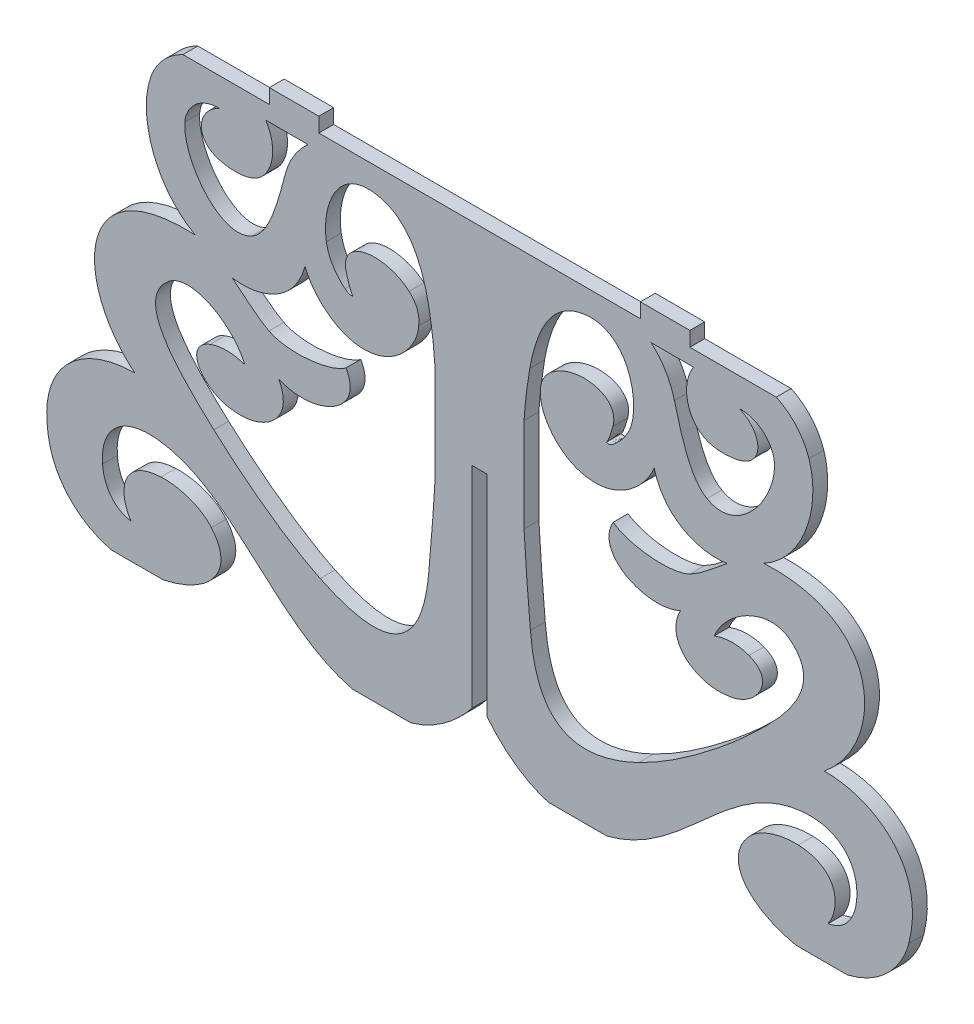
SolidWorks part; units mm, degrees
ref_plane "Plano frontal" through (0, 0, 0) normal (0, 0, 1) x (1, 0, 0)
ref_plane "Plano superior" through (0, 0, 0) normal (0, 1, 0) x (1, 0, 0)
ref_plane "Plano direito" through (0, 0, 0) normal (1, 0, 0) x (0, 0, -1)
sketch "Model" plane through (0, 0, 0) normal (0, 0, 1) x (1, 0, 0)
  line L0 (-25.299, -80.6801) -> (18.0344, -80.6801)
  line L21 (39.01, -143.3136) -> (45.9466, -143.3136)
  line L22 (36.3446, -80.6801) -> (24.701, -80.6801)
  line L23 (24.701, -80.6801) -> (24.701, -78.7123)
  line L24 (24.701, -78.7123) -> (18.0344, -78.7123)
  line L25 (18.0344, -78.7123) -> (18.0344, -80.6801)
  line L26 (-25.299, -80.6801) -> (-25.299, -78.7123)
  line L27 (-25.299, -78.7123) -> (-31.9656, -78.7123)
  line L28 (-31.9656, -78.7123) -> (-31.9656, -80.6801)
  line L29 (-31.9656, -80.6801) -> (-43.6092, -80.6801)
  line L30 (-53.2112, -143.3136) -> (-46.2746, -143.3136)
  line L31 (-20.7922, -143.3136) -> (-12.8827, -143.3136)
  line L32 (-4.6323, -137.4568) -> (-4.6323, -109.1511)
  line L33 (-4.6323, -109.1511) -> (-2.6323, -109.1511)
  line L34 (-2.6323, -109.1511) -> (-2.6323, -137.4568)
  line L35 (5.6181, -143.3136) -> (13.5276, -143.3136)
  line L36 (-26.7511, -82.7498) -> (-32.4569, -82.7498)
  line L37 (-9.6217, -113.0468) -> (-9.6217, -100.393)
  line L38 (19.4865, -82.7498) -> (25.1923, -82.7498)
  line L39 (2.3571, -113.0468) -> (2.3571, -100.393)
  spline S82 degree 3 poles (13.5276, -143.3136) (24.0999, -140.6337) (29.5908, -128.3406) (39.7847, -127.3008) knots 0 0 0 0 0.02439 0.02439 0.02439 0.02439
  spline S83 degree 3 poles (39.7847, -127.3008) (44.8462, -126.7846) (47.5126, -129.843) (47.1792, -133.8877) knots 0.02439 0.02439 0.02439 0.02439 0.04878 0.04878 0.04878 0.04878
  spline S84 degree 3 poles (47.1792, -133.8877) (46.9993, -136.07) (45.898, -138.1875) (43.3255, -138.6275) knots 0.04878 0.04878 0.04878 0.04878 0.073171 0.073171 0.073171 0.073171
  spline S85 degree 3 poles (43.3255, -138.6275) (45.091, -136.0452) (44.7729, -131.7145) (39.3053, -131.4591) knots 0.073171 0.073171 0.073171 0.073171 0.097561 0.097561 0.097561 0.097561
  spline S86 degree 3 poles (39.3053, -131.4591) (36.7984, -131.342) (33.9868, -132.244) (32.5083, -133.9746) knots 0.097561 0.097561 0.097561 0.097561 0.121951 0.121951 0.121951 0.121951
  spline S87 degree 3 poles (32.5083, -133.9746) (29.0675, -138.0023) (32.9753, -142.0567) (39.01, -143.3136) knots 0.121951 0.121951 0.121951 0.121951 0.146341 0.146341 0.146341 0.146341
  spline S88 degree 3 poles (45.9466, -143.3136) (50.593, -142.1908) (53.3599, -138.7763) (54.1991, -135.5231) knots 0.170732 0.170732 0.170732 0.170732 0.195122 0.195122 0.195122 0.195122
  spline S89 degree 3 poles (54.1991, -135.5231) (56.5947, -126.2354) (50.0219, -121.0373) (42.8047, -121.0878) knots 0.195122 0.195122 0.195122 0.195122 0.219512 0.219512 0.219512 0.219512
  spline S90 degree 3 poles (42.8047, -121.0878) (51.071, -114.4578) (51.1176, -100.1132) (34.6597, -100.9082) knots 0.219512 0.219512 0.219512 0.219512 0.243902 0.243902 0.243902 0.243902
  spline S91 degree 3 poles (34.6597, -100.9082) (39.9859, -98.0452) (42.4387, -90.8382) (40.748, -85.6548) knots 0.243902 0.243902 0.243902 0.243902 0.268293 0.268293 0.268293 0.268293
  spline S92 degree 3 poles (40.748, -85.6548) (40.1089, -83.6954) (38.6749, -81.7888) (36.3446, -80.6801) knots 0.268293 0.268293 0.268293 0.268293 0.292683 0.292683 0.292683 0.292683
  spline S94 degree 3 poles (-43.6092, -80.6801) (-45.9395, -81.7888) (-47.3735, -83.6954) (-48.0126, -85.6548) knots 0.512195 0.512195 0.512195 0.512195 0.536585 0.536585 0.536585 0.536585
  spline S95 degree 3 poles (-48.0126, -85.6548) (-49.7033, -90.8382) (-47.2505, -98.0452) (-41.9243, -100.9082) knots 0.536585 0.536585 0.536585 0.536585 0.560976 0.560976 0.560976 0.560976
  spline S96 degree 3 poles (-41.9243, -100.9082) (-58.3822, -100.1132) (-58.3356, -114.4578) (-50.0693, -121.0878) knots 0.560976 0.560976 0.560976 0.560976 0.585366 0.585366 0.585366 0.585366
  spline S97 degree 3 poles (-50.0693, -121.0878) (-57.2865, -121.0373) (-63.8593, -126.2354) (-61.4637, -135.5231) knots 0.585366 0.585366 0.585366 0.585366 0.609756 0.609756 0.609756 0.609756
  spline S98 degree 3 poles (-61.4637, -135.5231) (-60.6245, -138.7763) (-57.8576, -142.1908) (-53.2112, -143.3136) knots 0.609756 0.609756 0.609756 0.609756 0.634146 0.634146 0.634146 0.634146
  spline S99 degree 3 poles (-46.2746, -143.3136) (-40.2399, -142.0567) (-36.3321, -138.0023) (-39.7729, -133.9746) knots 0.658537 0.658537 0.658537 0.658537 0.682927 0.682927 0.682927 0.682927
  spline S100 degree 3 poles (-39.7729, -133.9746) (-41.2514, -132.244) (-44.063, -131.342) (-46.5699, -131.4591) knots 0.682927 0.682927 0.682927 0.682927 0.707317 0.707317 0.707317 0.707317
  spline S101 degree 3 poles (-46.5699, -131.4591) (-52.0375, -131.7145) (-52.3556, -136.0452) (-50.5901, -138.6275) knots 0.707317 0.707317 0.707317 0.707317 0.731707 0.731707 0.731707 0.731707
  spline S102 degree 3 poles (-50.5901, -138.6275) (-53.1626, -138.1875) (-54.2639, -136.07) (-54.4438, -133.8877) knots 0.731707 0.731707 0.731707 0.731707 0.756098 0.756098 0.756098 0.756098
  spline S103 degree 3 poles (-54.4438, -133.8877) (-54.7772, -129.843) (-52.1108, -126.7846) (-47.0493, -127.3008) knots 0.756098 0.756098 0.756098 0.756098 0.780488 0.780488 0.780488 0.780488
  spline S104 degree 3 poles (-47.0493, -127.3008) (-36.8554, -128.3406) (-31.3645, -140.6337) (-20.7922, -143.3136) knots 0.780488 0.780488 0.780488 0.780488 0.804878 0.804878 0.804878 0.804878
  spline S105 degree 3 poles (-12.8827, -143.3136) (-8.8659, -142.1463) (-6.0526, -139.244) (-4.6323, -137.4568) knots 0.829268 0.829268 0.829268 0.829268 0.853659 0.853659 0.853659 0.853659
  spline S106 degree 3 poles (-2.6323, -137.4568) (-1.212, -139.244) (1.6013, -142.1463) (5.6181, -143.3136) knots 0.926829 0.926829 0.926829 0.926829 0.95122 0.95122 0.95122 0.95122
  spline S107 degree 3 poles (-32.4569, -82.7498) (-31.1733, -84.7323) (-31.2313, -87.2662) (-32.4844, -89.0266) knots 0 0 0 0 0.111111 0.111111 0.111111 0.111111
  spline S108 degree 3 poles (-32.4844, -89.0266) (-33.3768, -90.2802) (-35.0403, -91.1102) (-37.9276, -90.6875) knots 0.111111 0.111111 0.111111 0.111111 0.222222 0.222222 0.222222 0.222222
  spline S109 degree 3 poles (-37.9276, -90.6875) (-42.1519, -90.0692) (-41.9903, -85.9673) (-38.6474, -84.4976) knots 0.222222 0.222222 0.222222 0.222222 0.333333 0.333333 0.333333 0.333333
  spline S110 degree 3 poles (-38.6474, -84.4976) (-41.6734, -84.4609) (-43.2427, -86.7759) (-43.3562, -88.4235) knots 0.333333 0.333333 0.333333 0.333333 0.444444 0.444444 0.444444 0.444444
  spline S111 degree 3 poles (-43.3562, -88.4235) (-43.6636, -92.8804) (-38.5123, -99.6442) (-34.2704, -97.1791) knots 0.444444 0.444444 0.444444 0.444444 0.555556 0.555556 0.555556 0.555556
  spline S112 degree 3 poles (-34.2704, -97.1791) (-32.5007, -96.1507) (-31.3381, -93.6932) (-29.8837, -87.9524) knots 0.555556 0.555556 0.555556 0.555556 0.666667 0.666667 0.666667 0.666667
  spline S113 degree 3 poles (-29.8837, -87.9524) (-29.3667, -85.9116) (-28.3138, -84.1273) (-26.7511, -82.7498) knots 0.666667 0.666667 0.666667 0.666667 0.777778 0.777778 0.777778 0.777778
  spline S114 degree 3 poles (-9.6217, -100.393) (-9.7726, -98.2023) (-10.0208, -96.045) (-10.3939, -93.9386) knots 0.041667 0.041667 0.041667 0.041667 0.083333 0.083333 0.083333 0.083333
  spline S115 degree 3 poles (-10.3939, -93.9386) (-11.331, -88.6476) (-13.5268, -84.1713) (-18.2928, -83.8913) knots 0.083333 0.083333 0.083333 0.083333 0.125 0.125 0.125 0.125
  spline S116 degree 3 poles (-18.2928, -83.8913) (-23.0171, -83.6137) (-24.9083, -88.9647) (-24.2808, -92.8525) knots 0.125 0.125 0.125 0.125 0.166667 0.166667 0.166667 0.166667
  spline S117 degree 3 poles (-24.2808, -92.8525) (-24.0259, -94.4318) (-23.2335, -95.8334) (-21.7588, -97.078) knots 0.166667 0.166667 0.166667 0.166667 0.208333 0.208333 0.208333 0.208333
  spline S118 degree 3 poles (-21.7588, -97.078) (-21.3405, -97.4311) (-20.9898, -97.5247) (-20.7021, -97.3929) knots 0.208333 0.208333 0.208333 0.208333 0.25 0.25 0.25 0.25
  spline S119 degree 3 poles (-20.7021, -97.3929) (-20.8973, -97.2341) (-21.1963, -96.5924) (-21.5905, -95.1207) knots 0.25 0.25 0.25 0.25 0.291667 0.291667 0.291667 0.291667
  spline S120 degree 3 poles (-21.5905, -95.1207) (-22.6756, -91.07) (-16.2984, -90.2558) (-13.1252, -93.083) knots 0.291667 0.291667 0.291667 0.291667 0.333333 0.333333 0.333333 0.333333
  spline S121 degree 3 poles (-13.1252, -93.083) (-12.1537, -93.9486) (-11.6464, -95.1051) (-11.8511, -96.4742) knots 0.333333 0.333333 0.333333 0.333333 0.375 0.375 0.375 0.375
  spline S122 degree 3 poles (-11.8511, -96.4742) (-11.9194, -98.9913) (-15.0834, -103.3668) (-20.0254, -102.8281) knots 0.375 0.375 0.375 0.375 0.416667 0.416667 0.416667 0.416667
  spline S123 degree 3 poles (-20.0254, -102.8281) (-23.5148, -102.4476) (-26.3139, -99.4595) (-27.1557, -97.1641) knots 0.416667 0.416667 0.416667 0.416667 0.458333 0.458333 0.458333 0.458333
  spline S124 degree 3 poles (-27.1557, -97.1641) (-28.5683, -102.4552) (-33.5101, -103.9638) (-36.9867, -103.4069) knots 0.458333 0.458333 0.458333 0.458333 0.5 0.5 0.5 0.5
  spline S125 degree 3 poles (-36.9867, -103.4069) (-35.3064, -104.7163) (-33.7715, -106.2083) (-32.007, -107.1244) knots 0.5 0.5 0.5 0.5 0.541667 0.541667 0.541667 0.541667
  spline S126 degree 3 poles (-32.007, -107.1244) (-29.3781, -108.4896) (-23.7227, -107.8286) (-21.6381, -106.2645) knots 0.541667 0.541667 0.541667 0.541667 0.583333 0.583333 0.583333 0.583333
  spline S127 degree 3 poles (-21.6381, -106.2645) (-18.9894, -110.8906) (-26.1931, -114.1757) (-30.699, -112.0561) knots 0.583333 0.583333 0.583333 0.583333 0.625 0.625 0.625 0.625
  spline S128 degree 3 poles (-30.699, -112.0561) (-28.4119, -116.3864) (-32.9424, -119.4988) (-37.1074, -118.7844) knots 0.625 0.625 0.625 0.625 0.666667 0.666667 0.666667 0.666667
  spline S129 degree 3 poles (-37.1074, -118.7844) (-40.7542, -118.4687) (-43.8613, -114.1754) (-39.9339, -112.6598) knots 0.666667 0.666667 0.666667 0.666667 0.708333 0.708333 0.708333 0.708333
  spline S130 degree 3 poles (-39.9339, -112.6598) (-38.6761, -112.1744) (-36.9586, -112.0849) (-35.2485, -112.716) knots 0.708333 0.708333 0.708333 0.708333 0.75 0.75 0.75 0.75
  spline S131 degree 3 poles (-35.2485, -112.716) (-36.9784, -108.7073) (-42.6099, -105.7375) (-45.5096, -108.0977) knots 0.75 0.75 0.75 0.75 0.791667 0.791667 0.791667 0.791667
  spline S132 degree 3 poles (-45.5096, -108.0977) (-50.1258, -111.855) (-44.9673, -117.3572) (-39.4446, -122.3875) knots 0.791667 0.791667 0.791667 0.791667 0.833333 0.833333 0.833333 0.833333
  spline S133 degree 3 poles (-39.4446, -122.3875) (-36.6658, -124.9185) (-30.845, -129.788) (-25.1107, -132.5742) knots 0.833333 0.833333 0.833333 0.833333 0.875 0.875 0.875 0.875
  spline S134 degree 3 poles (-25.1107, -132.5742) (-13.1524, -138.3844) (-10.9954, -130.4623) (-10.4758, -124.4534) knots 0.875 0.875 0.875 0.875 0.916667 0.916667 0.916667 0.916667
  spline S135 degree 3 poles (-10.4758, -124.4534) (-10.1517, -120.706) (-9.8219, -116.8755) (-9.6217, -113.0468) knots 0.916667 0.916667 0.916667 0.916667 1 1 1 1
  spline S136 degree 3 poles (25.1923, -82.7498) (23.9087, -84.7323) (23.9667, -87.2662) (25.2198, -89.0266) knots 0 0 0 0 0.111111 0.111111 0.111111 0.111111
  spline S137 degree 3 poles (25.2198, -89.0266) (26.1122, -90.2802) (27.7757, -91.1102) (30.663, -90.6875) knots 0.111111 0.111111 0.111111 0.111111 0.222222 0.222222 0.222222 0.222222
  spline S138 degree 3 poles (30.663, -90.6875) (34.8873, -90.0692) (34.7257, -85.9673) (31.3828, -84.4976) knots 0.222222 0.222222 0.222222 0.222222 0.333333 0.333333 0.333333 0.333333
  spline S139 degree 3 poles (31.3828, -84.4976) (34.4088, -84.4609) (35.9781, -86.7759) (36.0916, -88.4235) knots 0.333333 0.333333 0.333333 0.333333 0.444444 0.444444 0.444444 0.444444
  spline S140 degree 3 poles (36.0916, -88.4235) (36.399, -92.8804) (31.2477, -99.6442) (27.0058, -97.1791) knots 0.444444 0.444444 0.444444 0.444444 0.555556 0.555556 0.555556 0.555556
  spline S141 degree 3 poles (27.0058, -97.1791) (25.2361, -96.1507) (24.0735, -93.6932) (22.6191, -87.9524) knots 0.555556 0.555556 0.555556 0.555556 0.666667 0.666667 0.666667 0.666667
  spline S142 degree 3 poles (22.6191, -87.9524) (22.1021, -85.9116) (21.0492, -84.1273) (19.4865, -82.7498) knots 0.666667 0.666667 0.666667 0.666667 0.777778 0.777778 0.777778 0.777778
  spline S143 degree 3 poles (2.3571, -100.393) (2.508, -98.2023) (2.7562, -96.045) (3.1293, -93.9386) knots 0.041667 0.041667 0.041667 0.041667 0.083333 0.083333 0.083333 0.083333
  spline S144 degree 3 poles (3.1293, -93.9386) (4.0664, -88.6476) (6.2622, -84.1713) (11.0282, -83.8913) knots 0.083333 0.083333 0.083333 0.083333 0.125 0.125 0.125 0.125
  spline S145 degree 3 poles (11.0282, -83.8913) (15.7525, -83.6137) (17.6437, -88.9647) (17.0162, -92.8525) knots 0.125 0.125 0.125 0.125 0.166667 0.166667 0.166667 0.166667
  spline S146 degree 3 poles (17.0162, -92.8525) (16.7613, -94.4318) (15.9689, -95.8334) (14.4942, -97.078) knots 0.166667 0.166667 0.166667 0.166667 0.208333 0.208333 0.208333 0.208333
  spline S147 degree 3 poles (14.4942, -97.078) (14.0759, -97.4311) (13.7252, -97.5247) (13.4375, -97.3929) knots 0.208333 0.208333 0.208333 0.208333 0.25 0.25 0.25 0.25
  spline S148 degree 3 poles (13.4375, -97.3929) (13.6327, -97.2341) (13.9317, -96.5924) (14.3259, -95.1207) knots 0.25 0.25 0.25 0.25 0.291667 0.291667 0.291667 0.291667
  spline S149 degree 3 poles (14.3259, -95.1207) (15.411, -91.07) (9.0338, -90.2558) (5.8606, -93.083) knots 0.291667 0.291667 0.291667 0.291667 0.333333 0.333333 0.333333 0.333333
  spline S150 degree 3 poles (5.8606, -93.083) (4.8891, -93.9486) (4.3818, -95.1051) (4.5865, -96.4742) knots 0.333333 0.333333 0.333333 0.333333 0.375 0.375 0.375 0.375
  spline S151 degree 3 poles (4.5865, -96.4742) (4.6548, -98.9913) (7.8188, -103.3668) (12.7608, -102.8281) knots 0.375 0.375 0.375 0.375 0.416667 0.416667 0.416667 0.416667
  spline S152 degree 3 poles (12.7608, -102.8281) (16.2502, -102.4476) (19.0493, -99.4595) (19.8911, -97.1641) knots 0.416667 0.416667 0.416667 0.416667 0.458333 0.458333 0.458333 0.458333
  spline S153 degree 3 poles (19.8911, -97.1641) (21.3037, -102.4552) (26.2455, -103.9638) (29.7221, -103.4069) knots 0.458333 0.458333 0.458333 0.458333 0.5 0.5 0.5 0.5
  spline S154 degree 3 poles (29.7221, -103.4069) (28.0418, -104.7163) (26.5069, -106.2083) (24.7424, -107.1244) knots 0.5 0.5 0.5 0.5 0.541667 0.541667 0.541667 0.541667
  spline S155 degree 3 poles (24.7424, -107.1244) (22.1135, -108.4896) (16.4581, -107.8286) (14.3735, -106.2645) knots 0.541667 0.541667 0.541667 0.541667 0.583333 0.583333 0.583333 0.583333
  spline S156 degree 3 poles (14.3735, -106.2645) (11.7248, -110.8906) (18.9285, -114.1757) (23.4344, -112.0561) knots 0.583333 0.583333 0.583333 0.583333 0.625 0.625 0.625 0.625
  spline S157 degree 3 poles (23.4344, -112.0561) (21.1473, -116.3864) (25.6778, -119.4988) (29.8428, -118.7844) knots 0.625 0.625 0.625 0.625 0.666667 0.666667 0.666667 0.666667
  spline S158 degree 3 poles (29.8428, -118.7844) (33.4896, -118.4687) (36.5967, -114.1754) (32.6693, -112.6598) knots 0.666667 0.666667 0.666667 0.666667 0.708333 0.708333 0.708333 0.708333
  spline S159 degree 3 poles (32.6693, -112.6598) (31.4115, -112.1744) (29.694, -112.0849) (27.9839, -112.716) knots 0.708333 0.708333 0.708333 0.708333 0.75 0.75 0.75 0.75
  spline S160 degree 3 poles (27.9839, -112.716) (29.7138, -108.7073) (35.3453, -105.7375) (38.245, -108.0977) knots 0.75 0.75 0.75 0.75 0.791667 0.791667 0.791667 0.791667
  spline S161 degree 3 poles (38.245, -108.0977) (42.8612, -111.855) (37.7027, -117.3572) (32.18, -122.3875) knots 0.791667 0.791667 0.791667 0.791667 0.833333 0.833333 0.833333 0.833333
  spline S162 degree 3 poles (32.18, -122.3875) (29.4012, -124.9185) (23.5804, -129.788) (17.8461, -132.5742) knots 0.833333 0.833333 0.833333 0.833333 0.875 0.875 0.875 0.875
  spline S163 degree 3 poles (17.8461, -132.5742) (5.8878, -138.3844) (3.7308, -130.4623) (3.2112, -124.4534) knots 0.875 0.875 0.875 0.875 0.916667 0.916667 0.916667 0.916667
  spline S164 degree 3 poles (3.2112, -124.4534) (2.8871, -120.706) (2.5573, -116.8755) (2.3571, -113.0468) knots 0.916667 0.916667 0.916667 0.916667 1 1 1 1
extrude "Ressalto-extrusão1" add sketch "Model" along normal blind 2
